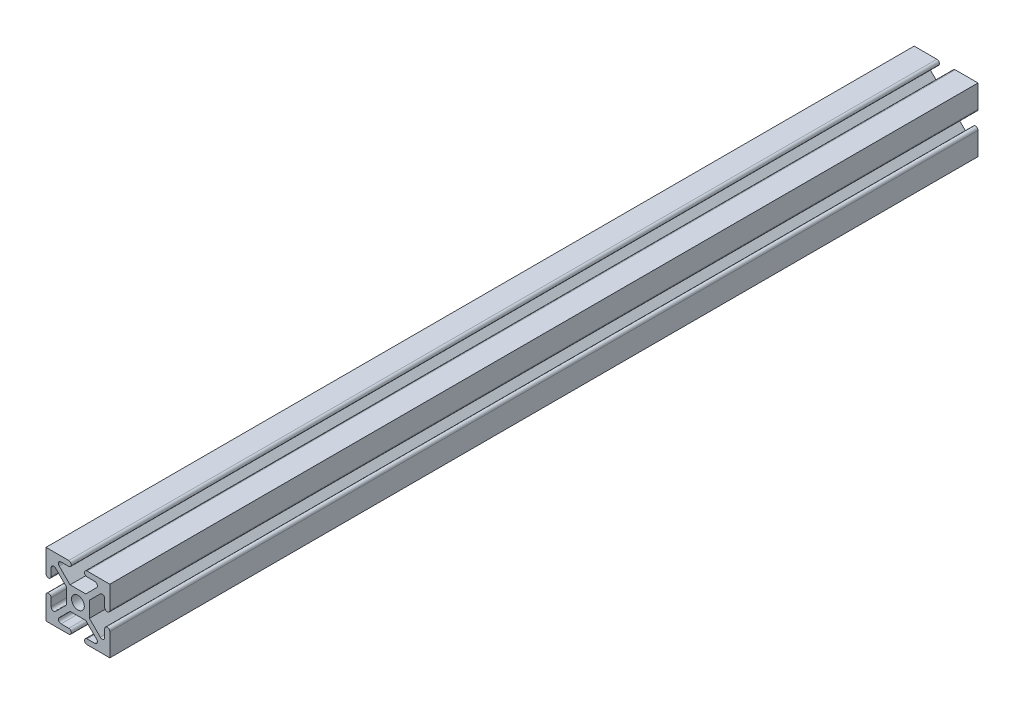
SolidWorks part; units mm, degrees
ref_plane "Front Plane" through (0, 0, 0) normal (0, 0, 1) x (1, 0, 0)
ref_plane "Top Plane" through (0, 0, 0) normal (0, 1, 0) x (1, 0, 0)
ref_plane "Right Plane" through (0, 0, 0) normal (1, 0, 0) x (0, 0, -1)
sketch "Sketch2" plane through (0, 0, 0) normal (0, 0, 1) x (1, 0, 0)
  line L0 (9.4142, 17) -> (5.1716, 21.2426)
  line L5 (9.4142, 17) -> (12.5, 17)
  line L9 (5.8995, 23) -> (8.8995, 23)
  line L10 (8.8995, 25) -> (0, 25)
  line L11 (0, 25) -> (8.8995, 25)
  line L12 (0, 16.1005) -> (0, 25)
  line L13 (2, 19.1005) -> (2, 16.1005)
  line L14 (8, 15.5858) -> (3.7574, 19.8284)
  line L15 (0, 25) -> (35355.3391, -35330.3391) construction
  line L16 (12.5, 12.5) -> (35367.8391, 35367.8391) construction
  line L17 (12.6363, 12.5) -> (50012.6363, 12.5) construction
  line L18 (12.5, 12.3637) -> (12.5, 50012.3637) construction
  line L19 (8, 15.5858) -> (8, 12.5)
  line L20 (9.4142, 8) -> (12.5, 8)
  line L21 (9.4142, 8) -> (5.1716, 3.7574)
  line L22 (5.8995, 2) -> (8.8995, 2)
  line L23 (8.8995, 0) -> (0, 0)
  line L24 (0, 8.8995) -> (0, 0)
  line L25 (2, 5.8995) -> (2, 8.8995)
  line L26 (8, 9.4142) -> (8, 12.5)
  line L27 (8, 9.4142) -> (3.7574, 5.1716)
  line L28 (15.5858, 17) -> (12.5, 17)
  line L29 (15.5858, 17) -> (19.8284, 21.2426)
  line L30 (19.1005, 23) -> (16.1005, 23)
  line L31 (16.1005, 25) -> (25, 25)
  line L32 (25, 16.1005) -> (25, 25)
  line L33 (23, 19.1005) -> (23, 16.1005)
  line L34 (17, 15.5858) -> (21.2426, 19.8284)
  line L35 (17, 15.5858) -> (17, 12.5)
  line L36 (17, 9.4142) -> (17, 12.5)
  line L37 (15.5858, 8) -> (12.5, 8)
  line L38 (17, 9.4142) -> (21.2426, 5.1716)
  line L39 (23, 5.8995) -> (23, 8.8995)
  line L40 (25, 8.8995) -> (25, 0)
  line L41 (16.1005, 0) -> (25, 0)
  line L42 (19.1005, 2) -> (16.1005, 2)
  line L43 (15.5858, 8) -> (19.8284, 3.7574)
  arc A0 (5.1716, 21.2426) -> (5.8995, 23) centre (5.8995, 21.9706) cw
  arc A1 (0, 16.1005) -> (2, 16.1005) centre (1, 16.1005) ccw
  arc A2 (8.8995, 25) -> (8.8995, 23) centre (8.8995, 24) cw
  arc A3 (3.7574, 19.8284) -> (2, 19.1005) centre (3.0294, 19.1005) ccw
  arc A4 (5.1716, 3.7574) -> (5.8995, 2) centre (5.8995, 3.0294) ccw
  arc A5 (8.8995, 0) -> (8.8995, 2) centre (8.8995, 1) ccw
  arc A6 (0, 8.8995) -> (2, 8.8995) centre (1, 8.8995) cw
  arc A7 (3.7574, 5.1716) -> (2, 5.8995) centre (3.0294, 5.8995) cw
  arc A8 (19.8284, 21.2426) -> (19.1005, 23) centre (19.1005, 21.9706) ccw
  arc A9 (16.1005, 25) -> (16.1005, 23) centre (16.1005, 24) ccw
  arc A10 (25, 16.1005) -> (23, 16.1005) centre (24, 16.1005) cw
  arc A11 (21.2426, 19.8284) -> (23, 19.1005) centre (21.9706, 19.1005) cw
  arc A12 (19.8284, 3.7574) -> (19.1005, 2) centre (19.1005, 3.0294) cw
  arc A13 (21.2426, 5.1716) -> (23, 5.8995) centre (21.9706, 5.8995) ccw
  arc A14 (25, 8.8995) -> (23, 8.8995) centre (24, 8.8995) ccw
  arc A15 (16.1005, 0) -> (16.1005, 2) centre (16.1005, 1) cw
  circle A16 centre (12.5, 12.5) radius 2.5
  dimension "D14" = 5
  dimension "D2" = 1.0294
  dimension "D3" = 12.5
  dimension "D4" = 12.5
  dimension "D5" = 17.6777
  dimension "D7" = 45
  dimension "D9" = 12.5
  dimension "D10" = 6
  dimension "D11" = 3
  dimension "D12" = 1
  dimension "D13" = 2
extrude "Boss-Extrude1" add sketch "Sketch2" along normal blind 340 contours A15 L41 L40 A14 L39 A13 L38 L36 L35 L34 A11 L33 A10 L32 L31 A9 L30 A8 L29 L28 L5 L0 A0 L9 A2 L10 L12 A1 L13 A3 L14 L19 L26 L27 A7 L25 A6 L24 L23 A5 L22 A4 L21 L20 L37 L43 A12 L42 A16
